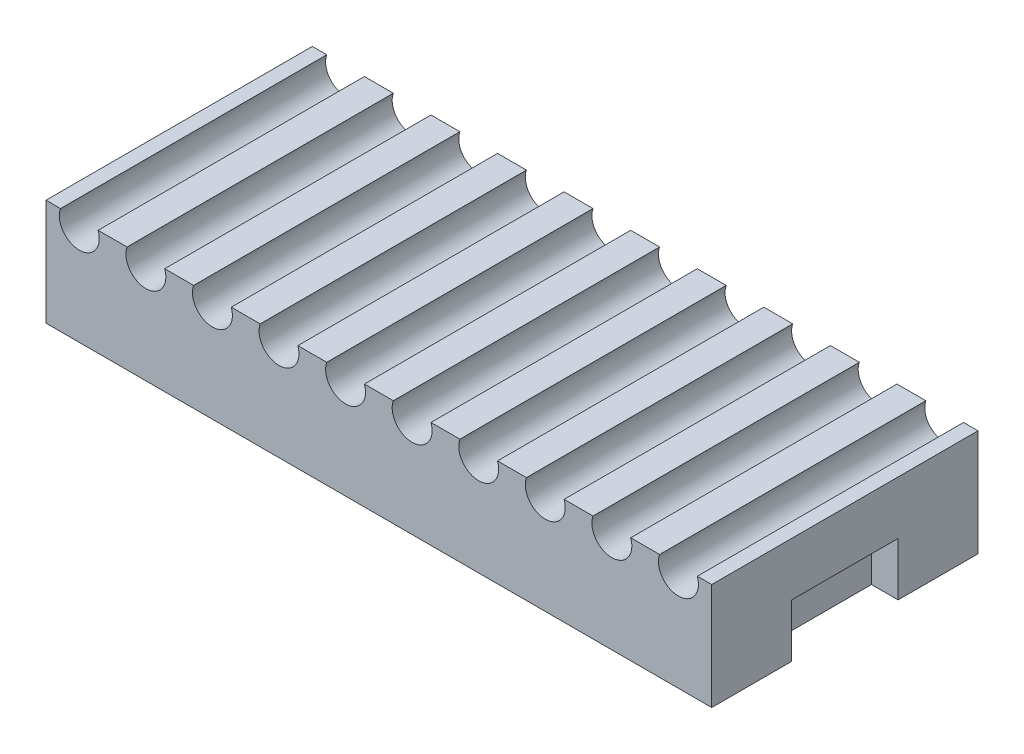
SolidWorks part; units mm, degrees
ref_plane "Front Plane" through (0, 0, 0) normal (0, 0, 1) x (1, 0, 0)
ref_plane "Top Plane" through (0, 0, 0) normal (0, 1, 0) x (1, 0, 0)
ref_plane "Right Plane" through (0, 0, 0) normal (1, 0, 0) x (0, 0, -1)
sketch "Sketch1" plane through (0, 0, 0) normal (0, 0, 1) x (1, 0, 0)
  line L1 (-12.5, 2) -> (12.5, 2)
  line L2 (-12.5, 2) -> (-12.5, -2)
  line L3 (-12.5, -2) -> (12.5, -2)
  line L4 (12.5, 2) -> (12.5, -2)
  line L5 (-12.5, 2) -> (12.5, -2) construction
  line L6 (-12.5, -2) -> (12.5, 2) construction
  point P0 (0, 0)
  dimension "D1" = 4
  dimension "D2" = 25
extrude "Boss-Extrude1" add sketch "Sketch1" along normal blind 10
sketch "Sketch2" plane through (0, 0, 0) normal (0, 0, -1) x (-1, 0, 0)
  line L2 (-12.5, 2) -> (12.5, 2) construction
  line L3 (-11.25, 1.75) -> (11.25, 1.75) construction
  circle A0 centre (-11.25, 1.75) radius 0.75
  circle A1 centre (-8.75, 1.75) radius 0.75
  circle A2 centre (-6.25, 1.75) radius 0.75
  circle A3 centre (-3.75, 1.75) radius 0.75
  circle A4 centre (-1.25, 1.75) radius 0.75
  circle A5 centre (1.25, 1.75) radius 0.75
  circle A6 centre (3.75, 1.75) radius 0.75
  circle A7 centre (6.25, 1.75) radius 0.75
  circle A8 centre (8.75, 1.75) radius 0.75
  circle A9 centre (11.25, 1.75) radius 0.75
  point P2 (-3.734, 0.5)
  point P3 (0, 2)
  point P4 (0, 1.75)
  dimension "D1" = 1.5
  dimension "D5" = 0.25
  dimension "D3" = 10
  dimension "D4" = 2.5
extrude "Cut-Extrude1" cut sketch "Sketch2" against normal through all
sketch "Sketch4" plane through (12.5, 0, 0) normal (1, 0, 0) x (0, 0, -1)
  line L0 (-10, 2) -> (0, 2) construction
  line L1 (-7, 0) -> (-3, 0)
  line L2 (-7, 0) -> (-7, -2)
  line L3 (-7, -2) -> (-3, -2)
  line L4 (-3, 0) -> (-3, -2)
  line L5 (-7, 0) -> (-3, -2) construction
  line L6 (-7, -2) -> (-3, 0) construction
  line L7 (-10, -2) -> (0, -2) construction
  point P0 (-5, -1)
  point P5 (0, 0)
  point P8 (-5, 2)
  dimension "D1" = 2
  dimension "D2" = 4
extrude "Cut-Extrude2" cut sketch "Sketch4" against normal blind 1
ref_plane "Plane1" through (0, 0, 0) normal (1, 0, 0) x (0, 0, -1)
mirror "Mirror1" about plane through (0, 0, 0) normal (1, 0, 0) of "Cut-Extrude2"
